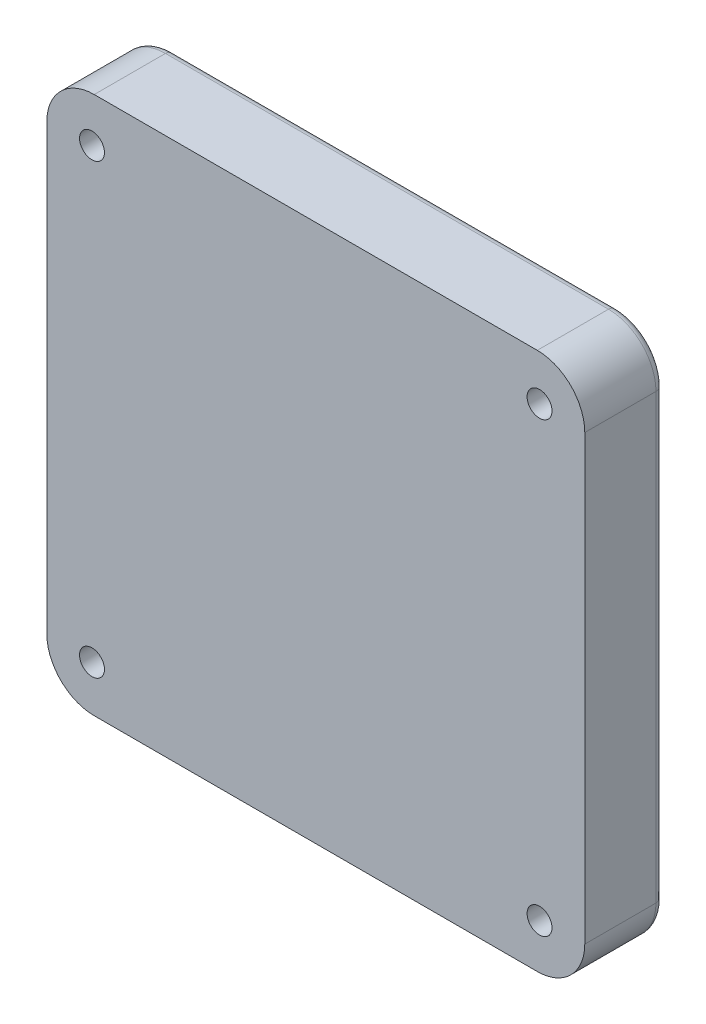
SolidWorks part; units mm, degrees
ref_plane "Front Plane" through (0, 0, 0) normal (0, 0, 1) x (1, 0, 0)
ref_plane "Top Plane" through (0, 0, 0) normal (0, 1, 0) x (1, 0, 0)
ref_plane "Right Plane" through (0, 0, 0) normal (1, 0, 0) x (0, 0, -1)
sketch "Sketch1" plane through (0, 0, -96.9958) normal (0, 0, -1) x (-1, 0, 0)
  line L1 (-61.0728, 13.2587) -> (-117.0728, 13.2587)
  line L2 (-55.0728, 19.2587) -> (-55.0728, 75.2587)
  line L3 (-61.0728, 81.2587) -> (-117.0728, 81.2587)
  line L4 (-123.0728, 19.2587) -> (-123.0728, 75.2587)
  line L5 (-55.0728, 13.2587) -> (-123.0728, 81.2587) construction
  line L6 (-55.0728, 81.2587) -> (-123.0728, 13.2587) construction
  arc A0 (-117.0728, 13.2587) -> (-123.0728, 19.2587) centre (-117.0728, 19.2587) cw
  arc A1 (-61.0728, 13.2587) -> (-55.0728, 19.2587) centre (-61.0728, 19.2587) ccw
  arc A2 (-55.0728, 75.2587) -> (-61.0728, 81.2587) centre (-61.0728, 75.2587) ccw
  arc A3 (-117.0728, 81.2587) -> (-123.0728, 75.2587) centre (-117.0728, 75.2587) ccw
  circle A4 centre (-117.3571, 75.543) radius 1.575
  circle A5 centre (-60.7885, 75.543) radius 1.575
  circle A6 centre (-60.7885, 18.9744) radius 1.575
  circle A7 centre (-117.3571, 18.9744) radius 1.575
  point P0 (-89.0728, 47.2587)
  point P30 (-89.0728, 47.2587)
  dimension "D3" = 6
  dimension "D4" = 3.15
  dimension "D1" = 68
  dimension "D2" = 68
  dimension "D5" = 4
extrude "Boss-Extrude1" add sketch "Sketch1" along normal blind 10
fillet "Fillet1" radius 1 8 edges at (121.3154, 79.5013, -106.9958) (89.0728, 81.2587, -106.9958) (56.8302, 79.5013, -106.9958) (55.0728, 47.2587, -106.9958) (56.8302, 15.0161, -106.9958) (89.0728, 13.2587, -106.9958) (121.3154, 15.0161, -106.9958) (123.0728, 47.2587, -106.9958)
